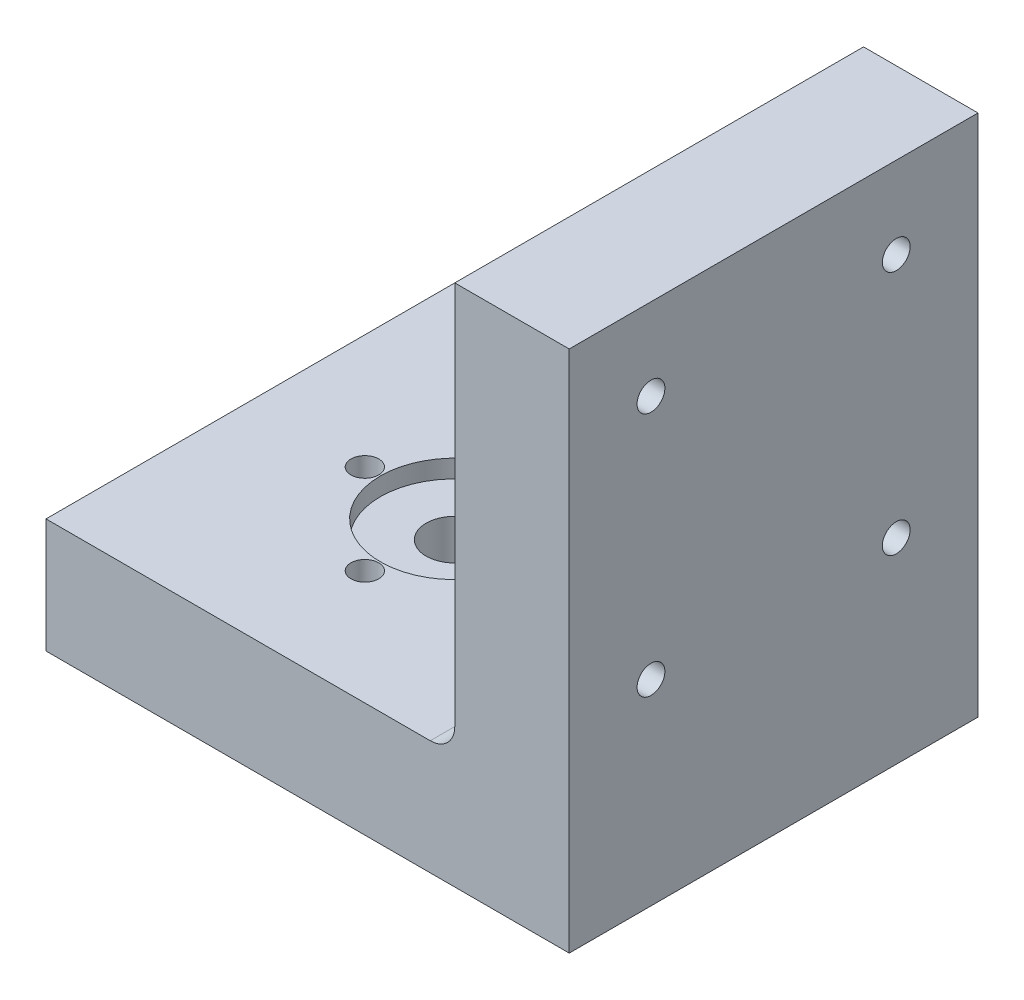
SolidWorks part; units mm, degrees
ref_plane "Front Plane" through (0, 0, 0) normal (0, 0, 1) x (1, 0, 0)
ref_plane "Top Plane" through (0, 0, 0) normal (0, 1, 0) x (1, 0, 0)
ref_plane "Right Plane" through (0, 0, 0) normal (1, 0, 0) x (0, 0, -1)
sketch "Sketch2" plane through (0, 0, 0) normal (0, 0, 1) x (1, 0, 0)
  line L1 (-34, 7) -> (16, 7)
  line L2 (-34, 7) -> (-34, -7)
  line L3 (-34, -7) -> (30, -7)
  line L4 (30, 7) -> (30, -7)
  line L8 (30, 7) -> (30, 57)
  line L9 (30, 57) -> (16, 57)
  line L10 (16, 7) -> (16, 57)
  point P0 (0, 0)
  dimension "D3" = 50
  dimension "D4" = 14
  dimension "D1" = 50
  dimension "D2" = 14
extrude "Boss-Extrude1" add sketch "Sketch2" along normal mid plane 50
sketch "Sketch3" plane through (0, 7, 0) normal (0, 1, 0) x (1, 0, 0)
  line L0 (-9, 25) -> (-9, -25) construction
  line L1 (16, 25) -> (-34, 25) construction
  line L2 (16, -25) -> (-34, -25) construction
  line L3 (-34, 0) -> (16, 0) construction
  line L4 (-34, -25) -> (-34, 25) construction
  line L5 (16, -25) -> (16, 25) construction
  circle A0 centre (-9, 0) radius 3.5
  dimension "D1" = 7
extrude "Cut-Extrude1" cut sketch "Sketch3" against normal through all
sketch "Sketch4" plane through (0, 7, 0) normal (0, 1, 0) x (1, 0, 0)
  circle A0 centre (-9, 0) radius 11 construction
  circle A1 centre (-9, 11) radius 1.7
  circle A2 centre (-20, 0) radius 1.7
  circle A3 centre (-9, -11) radius 1.7
  circle A4 centre (2, 0) radius 1.7
  dimension "D1" = 22
  dimension "D3" = 4
extrude "Cut-Extrude2" cut sketch "Sketch4" against normal through all
sketch "Sketch5" plane through (16, 0, 0) normal (-1, 0, 0) x (0, 0, 1)
  line L0 (25, 57) -> (-25, 57) construction
  line L1 (-25, 57) -> (-25, 7) construction
  line L6 (25, 7) -> (-25, 7) construction
  line L7 (25, 57) -> (25, 7) construction
  circle A0 centre (-15, 47) radius 1.7
  circle A1 centre (-15, 17) radius 1.7
  circle A2 centre (15, 17) radius 1.7
  circle A3 centre (15, 47) radius 1.7
  point P7 (0, 32)
  point P15 (0, 32)
  dimension "D3" = 4
  dimension "D6" = 3.4
  dimension "D1" = 10
  dimension "D2" = 10
  dimension "D4" = 10
  dimension "D5" = 10
extrude "Cut-Extrude3" cut sketch "Sketch5" against normal through all
sketch "Sketch6" plane through (0, 7, 0) normal (0, 1, 0) x (1, 0, 0)
  circle A0 centre (-9, 0) radius 9.1
  dimension "D1" = 18.2
extrude "Cut-Extrude4" cut sketch "Sketch6" against normal blind 2.2
fillet "Fillet1" radius 3 1 edges at (16, 7, 0)
equation "\"width\"= 50"
equation "\"length1\"= 50"
equation "\"length2\"= 50"
equation "\"thick\"= 14"
equation "\"boltholedia\"= 3.4"
equation "\"motorbcd\"= 22"
equation "\"shaftholedia\"=7"
equation "\"walledge\"= 10"
equation "\"fillet\" = 3"
equation "\"D3@Sketch2\"=\"length2\""
equation "\"D4@Sketch2\"=\"thick\""
equation "\"D1@Boss-Extrude1\"=\"width\""
equation "\"D1@Sketch2\"=\"length1\""
equation "\"D2@Sketch2\"=\"thick\""
equation "\"D1@Sketch3\"=\"shaftholedia\""
equation "\"D1@Sketch4\"=\"motorbcd\""
equation "\"D2@Sketch4\"=\"boltholedia\""
equation "\"D1@Sketch5\"=\"walledge\""
equation "\"D2@Sketch5\"=\"walledge\""
equation "\"D4@Sketch5\"=\"walledge\""
equation "\"D5@Sketch5\"=\"walledge\""
equation "\"D6@Sketch5\"=\"boltholedia\""
equation "\"motorbossdia\" = 18.2"
equation "\"motorbossdepth\"= 2.2"
equation "\"D1@Sketch6\"=\"motorbossdia\""
equation "\"D1@Cut-Extrude4\"=\"motorbossdepth\""
equation "\"D1@Fillet1\"=\"fillet\""
